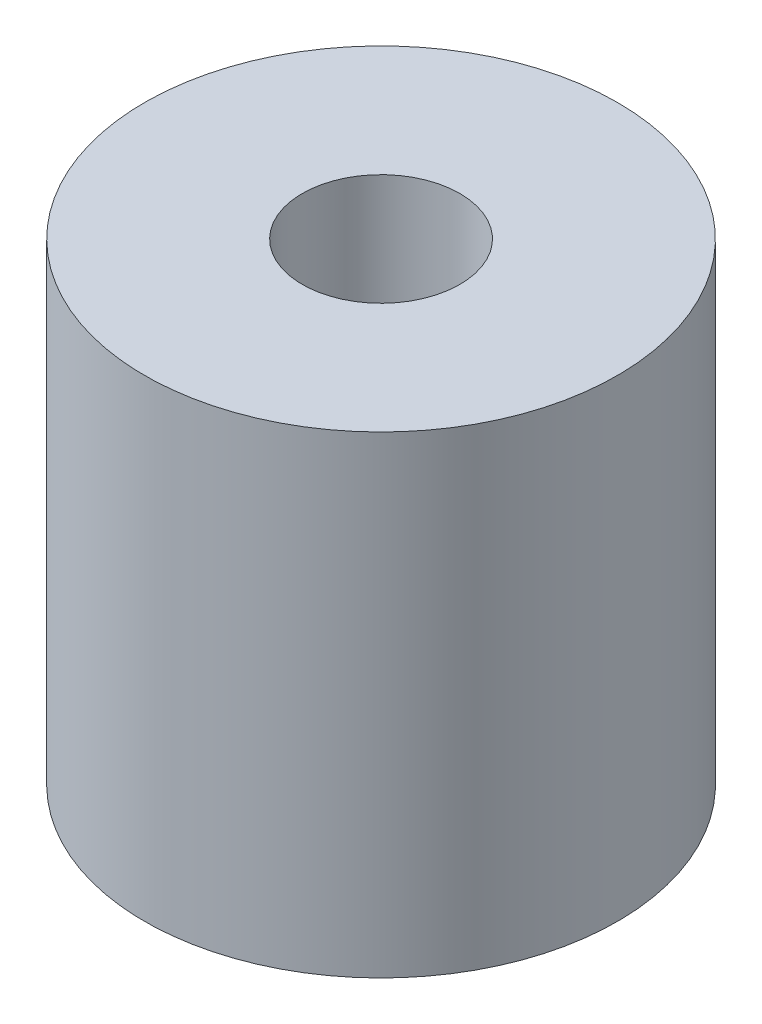
SolidWorks part; units mm, degrees
ref_plane "Front Plane" through (0, 0, 0) normal (0, 0, 1) x (1, 0, 0)
ref_plane "Top Plane" through (0, 0, 0) normal (0, 1, 0) x (1, 0, 0)
ref_plane "Right Plane" through (0, 0, 0) normal (1, 0, 0) x (0, 0, -1)
sketch "Sketch1" plane through (0, 0, 0) normal (0, 0, 1) x (1, 0, 0)
  line L0 (0, -40) -> (0, 40) construction
  line L1 (10, -30) -> (30, -30)
  line L2 (30, -30) -> (30, 30)
  line L3 (30, 30) -> (10, 30)
  line L4 (10, 30) -> (10, -30)
revolve "Revolve1" add sketch "Sketch1" angle 360 about L0
